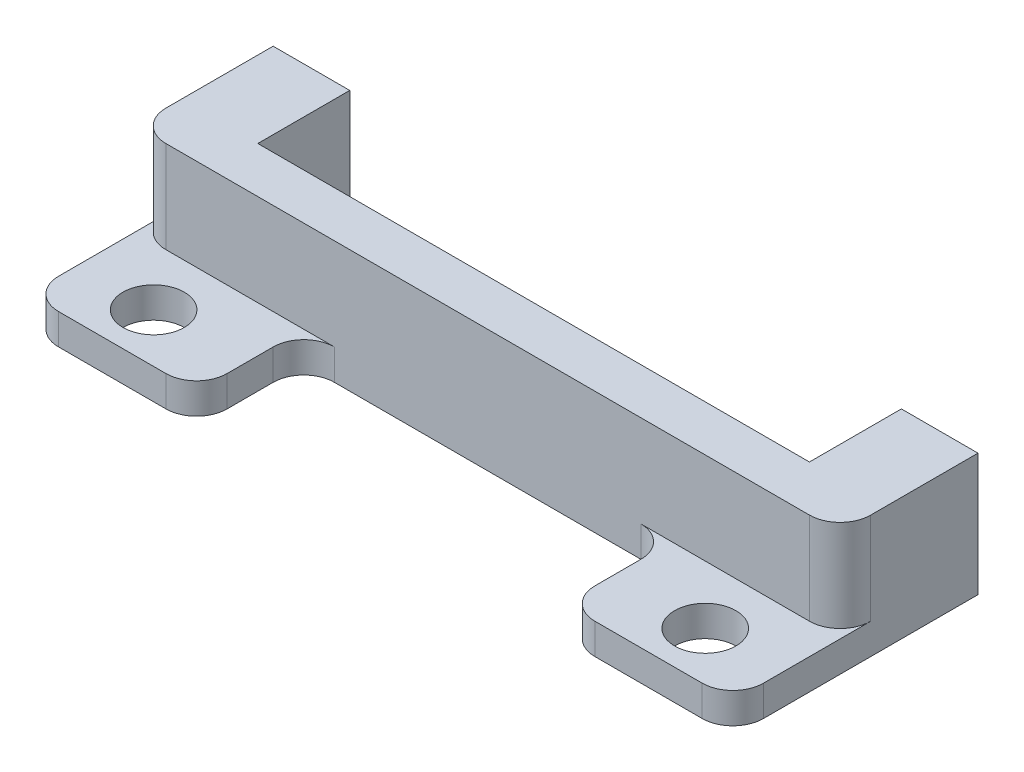
SolidWorks part; units mm, degrees
ref_plane "Front Plane" through (0, 0, 0) normal (0, 0, 1) x (1, 0, 0)
ref_plane "Top Plane" through (0, 0, 0) normal (0, 1, 0) x (1, 0, 0)
ref_plane "Right Plane" through (0, 0, 0) normal (1, 0, 0) x (0, 0, -1)
sketch "Sketch1" plane through (0, 0, 0) normal (0, 1, 0) x (1, 0, 0)
  line L0 (0, 0) -> (5, 0)
  line L1 (5, 0) -> (5, -6)
  line L2 (5, -6) -> (41, -6)
  line L3 (41, -6) -> (41, 0)
  line L4 (41, 0) -> (46, 0)
  line L5 (46, 0) -> (46, -16)
  line L7 (0, -16) -> (0, 0)
  line L11 (0, -16) -> (46, -16)
  dimension "D1" = 36
  dimension "D2" = 5
  dimension "D3" = 5
  dimension "D4" = 6
  dimension "D5" = 16
extrude "Boss-Extrude1" add sketch "Sketch1" along normal blind 2
sketch "Sketch2" plane through (0, 2, 0) normal (0, 1, 0) x (1, 0, 0)
  line L0 (0, -9) -> (46, -9)
  line L8 (0, 0) -> (0, -16)
  line L9 (0, -16) -> (46, -16)
  line L10 (46, -16) -> (46, 0)
  line L11 (46, 0) -> (41, 0)
  line L12 (41, 0) -> (41, -6)
  line L13 (41, -6) -> (5, -6)
  line L14 (5, -6) -> (5, 0)
  line L15 (5, 0) -> (0, 0)
  line L16 (0, 0) -> (0, -16)
  line L17 (0, -16) -> (46, -16)
  line L18 (46, -16) -> (46, 0)
  line L19 (46, 0) -> (41, 0)
  line L20 (41, 0) -> (41, -6)
  line L21 (41, -6) -> (5, -6)
  line L22 (5, -6) -> (5, 0)
  line L23 (5, 0) -> (0, 0)
  line M10 (0, 0) -> (0, -16)
  line M12 (46, -16) -> (46, 0)
  line M13 (46, 0) -> (41, 0)
  line M14 (41, 0) -> (41, -6)
  line M15 (41, -6) -> (5, -6)
  line M16 (5, -6) -> (5, 0)
  line M17 (5, 0) -> (0, 0)
  dimension "D2" = 7
  dimension "D1" = 0
extrude "Boss-Extrude2" add sketch "Sketch2" along normal blind 6 contours L0 M10 M12 M13 M14 M15 M16 M17 | L16 L17 L18 L19 L20 L21 L22 L23
fillet "Fillet1" radius 2 4 edges at (0, 1, 16) (46, 5, 9) (0, 5, 9) (46, 1, 16)
sketch "Sketch4" plane through (0, 2, 0) normal (0, 1, 0) x (1, 0, 0)
  line L0 (0, -7) -> (0, -14) construction
  line L2 (2, -16) -> (44, -16) construction
  line L3 (23, -16) -> (23, -9) construction
  line L4 (2, -9) -> (44, -9) construction
  line L5 (41, -6) -> (41, -12.8) construction
  circle A0 centre (5, -12.8) radius 2
  circle A1 centre (41, -12.8) radius 2
  dimension "D1" = 4
  dimension "D2" = 5
  dimension "D3" = 3.2
extrude "Cut-Extrude1" cut sketch "Sketch4" against normal through all
sketch "Sketch7" plane through (0, 2, 0) normal (0, 1, 0) x (1, 0, 0)
  line L0 (23, -16) -> (23, -9) construction
  line L1 (2, -16) -> (44, -16) construction
  line L2 (2, -9) -> (44, -9) construction
  line L3 (11, -16) -> (11, -9)
  line L4 (11, -16) -> (35, -16)
  line L5 (11, -9) -> (35, -9)
  line L6 (35, -16) -> (35, -9)
  dimension "D1" = 12
extrude "Cut-Extrude2" cut sketch "Sketch7" against normal through all
fillet "Fillet2" radius 2 4 edges at (35, 1, 9) (35, 1, 16) (11, 1, 9) (11, 1, 16)
